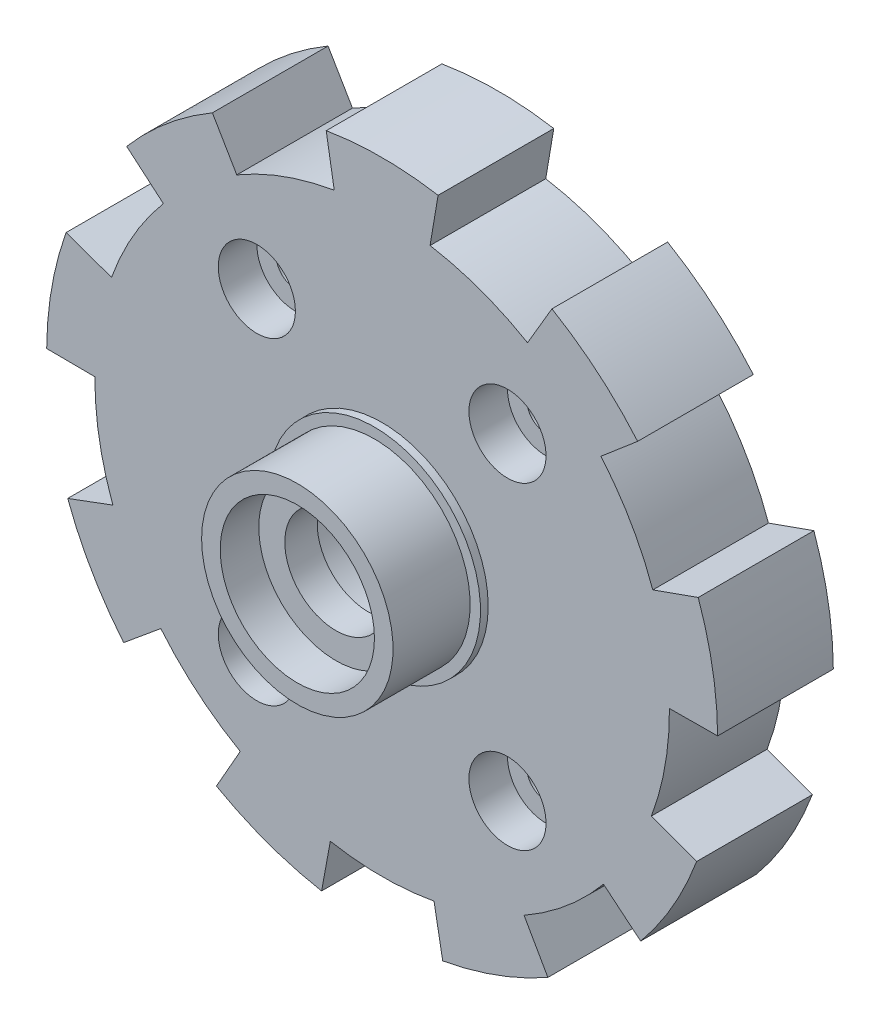
SolidWorks part; units mm, degrees
ref_plane "Plan de face" through (0, 0, 0) normal (0, 0, 1) x (1, 0, 0)
ref_plane "Plan de dessus" through (0, 0, 0) normal (0, 1, 0) x (1, 0, 0)
ref_plane "Plan de droite" through (0, 0, 0) normal (1, 0, 0) x (0, 0, -1)
sketch "Esquisse1" plane through (0, 0, 0) normal (0, 0, 1) x (1, 0, 0)
  line L0 (0, -10.7359) -> (0, 25.0521) construction
  line L1 (-11.2554, 0) -> (10.9091, 0) construction
  line L2 (2.9018, 17.1563) -> (0, 0) construction
  line L3 (0, 0) -> (-2.9018, 17.1563) construction
  line L4 (0, 0) -> (-8.805, 15.0077) construction
  line L5 (2.9018, 17.1563) -> (2.4849, 14.6913)
  line L6 (-2.9018, 17.1563) -> (-2.4849, 14.6913)
  line L7 (8.805, 15.0077) -> (7.5399, 12.8515)
  line L8 (13.2508, 11.2773) -> (11.3469, 9.657)
  line L9 (16.3918, 5.8369) -> (14.0367, 4.9982)
  line L10 (17.3996, 0.1215) -> (14.8996, 0.104)
  line L11 (16.3087, -6.0652) -> (13.9655, -5.1937)
  line L12 (13.4069, -11.0912) -> (11.4806, -9.4976)
  line L13 (8.5946, -15.1292) -> (7.3597, -12.9555)
  line L14 (3.141, -17.1141) -> (2.6897, -14.6552)
  line L15 (-3.141, -17.1141) -> (-2.6897, -14.6552)
  line L16 (-8.5946, -15.1292) -> (-7.3597, -12.9555)
  line L17 (-13.4069, -11.0912) -> (-11.4806, -9.4976)
  line L18 (-16.3087, -6.0652) -> (-13.9655, -5.1937)
  line L19 (-17.3996, 0.1215) -> (-14.8996, 0.104)
  line L20 (-16.3918, 5.8369) -> (-14.0367, 4.9982)
  line L21 (-13.2508, 11.2773) -> (-11.3469, 9.657)
  line L39 (-8.805, 15.0077) -> (-7.5399, 12.8515)
  arc A0 (2.9018, 17.1563) -> (-2.9018, 17.1563) centre (0, 0) ccw
  arc A1 (-2.4849, 14.6913) -> (-7.5399, 12.8515) centre (0, 0) ccw
  arc A2 (7.5399, 12.8515) -> (2.4849, 14.6913) centre (0, 0) ccw
  arc A3 (13.2508, 11.2773) -> (8.805, 15.0077) centre (0, 0) ccw
  arc A4 (14.0367, 4.9982) -> (11.3469, 9.657) centre (0, 0) ccw
  arc A5 (17.3996, 0.1215) -> (16.3918, 5.8369) centre (0, 0) ccw
  arc A6 (13.9655, -5.1937) -> (14.8996, 0.104) centre (0, 0) ccw
  arc A7 (13.4069, -11.0912) -> (16.3087, -6.0652) centre (0, 0) ccw
  arc A8 (7.3597, -12.9555) -> (11.4806, -9.4976) centre (0, 0) ccw
  arc A9 (3.141, -17.1141) -> (8.5946, -15.1292) centre (0, 0) ccw
  arc A10 (-2.6897, -14.6552) -> (2.6897, -14.6552) centre (0, 0) ccw
  arc A11 (-8.5946, -15.1292) -> (-3.141, -17.1141) centre (0, 0) ccw
  arc A12 (-11.4806, -9.4976) -> (-7.3597, -12.9555) centre (0, 0) ccw
  arc A13 (-16.3087, -6.0652) -> (-13.4069, -11.0912) centre (0, 0) ccw
  arc A14 (-14.8996, 0.104) -> (-13.9655, -5.1937) centre (0, 0) ccw
  arc A15 (-16.3918, 5.8369) -> (-17.3996, 0.1215) centre (0, 0) ccw
  arc A16 (-11.3469, 9.657) -> (-14.0367, 4.9982) centre (0, 0) ccw
  arc A17 (-8.805, 15.0077) -> (-13.2508, 11.2773) centre (0, 0) ccw
  circle A36 centre (-6.5, 8.25) radius 1
  circle A37 centre (-6.5, -8.25) radius 1
  circle A38 centre (6.5, -8.25) radius 1
  circle A39 centre (6.5, 8.25) radius 1
  point P56 (0, 0)
  point P99 (0, 0)
  dimension "D1" = 34.8
  dimension "D2" = 29.8
  dimension "D7" = 2
  dimension "D3" = 9.6
  dimension "D4" = 19.2
  dimension "D5" = 20.8
  dimension "D8" = 13
  dimension "D9" = 16.5
  dimension "D6" = 9
extrude "Boss.-Extru.2" add sketch "Esquisse1" along normal blind 6 contours L39 A17 L21 A16 L20 A15 L19 A14 L18 A13 L17 A12 L16 A11 L15 A10 L14 A9 L13 A8 L12 A7 L11 A6 L10 A5 L9 A4 L8 A3 L7 A2 L5 A0 L6 A1 A37 A36 A38 A39
sketch "Esquisse3" plane through (0, 0, 0) normal (0, 1, 0) x (1, 0, 0)
  line L0 (0, 3.6529) -> (0, -11.2429) construction
  line L1 (0, -6) -> (-5.5, -6)
  line L2 (-5.5, -6) -> (-5.5, -6.4)
  line L3 (-5.5, -6.4) -> (-4.965, -6.4)
  line L4 (-4.965, -6.4) -> (-4.965, -10.4)
  line L5 (-4.965, -10.4) -> (0, -10.4)
  line L6 (0, -10.4) -> (0, -6)
  line L7 (-2.9018, -6) -> (2.9018, -6) construction
  dimension "D1" = 4
  dimension "D2" = 0.4
  dimension "D3" = 9.93
  dimension "D4" = 11
revolve "Révolution1" add sketch "Esquisse3" angle 360 about L0
sketch "Esquisse4" plane through (0, 0, 0) normal (0, 1, 0) x (1, 0, 0)
  line L0 (0, -13.1575) -> (0, 3.663) construction
  line L1 (-2.65, -6.72) -> (-2.65, -8.4)
  line L2 (-2.65, -6.72) -> (-4, -6.72)
  line L3 (-4, -6.72) -> (-4, -4.72)
  line L4 (-4, -4.72) -> (-8, -4.72)
  line L5 (-12.6, -2.5) -> (-12.6, 0)
  line L7 (-2.65, -8.4) -> (-4, -8.4)
  line L8 (-4, -8.4) -> (-4, -10.4)
  line L9 (-4.965, -10.4) -> (4.965, -10.4) construction
  line L10 (-4, -10.4) -> (0, -10.4)
  line L11 (0, -10.4) -> (0, 0)
  line L12 (0, 0) -> (-12.6, 0)
  line L13 (-8, -4.72) -> (-8, -2.5)
  line L14 (-8, -2.5) -> (-12.6, -2.5)
  line L15 (-8.805, 0) -> (-13.2508, 0) construction
  dimension "D1" = 8
  dimension "D2" = 2
  dimension "D3" = 25.2
  dimension "D4" = 5.3
  dimension "D5" = 5.68
  dimension "D6" = 2.5
  dimension "D7" = 16
revolve "Enlèvement de matière-Révolution1" cut sketch "Esquisse4" angle 360 about L0
sketch "Esquisse5" plane through (0, 0, 6) normal (0, 0, 1) x (1, 0, 0)
  circle A0 centre (-6.5, 8.25) radius 2
  dimension "D1" = 4
extrude "Enlèv. mat.-Extru.1" cut sketch "Esquisse5" against normal blind 2
mirror "Symétrie1" about plane through (0, 0, 0) normal (0, 1, 0) of "Enlèv. mat.-Extru.1"
mirror "Symétrie2" about plane through (0, 0, 0) normal (1, 0, 0) of "Symétrie1", "Enlèv. mat.-Extru.1"
equation "\"D4@Esquisse1\"=\"D3@Esquisse1\"*2"
equation "\"D5@Esquisse1\"=40-\"D4@Esquisse1\""
equation "\"D2@Esquisse1\"=\"D1@Esquisse1\"-5"
